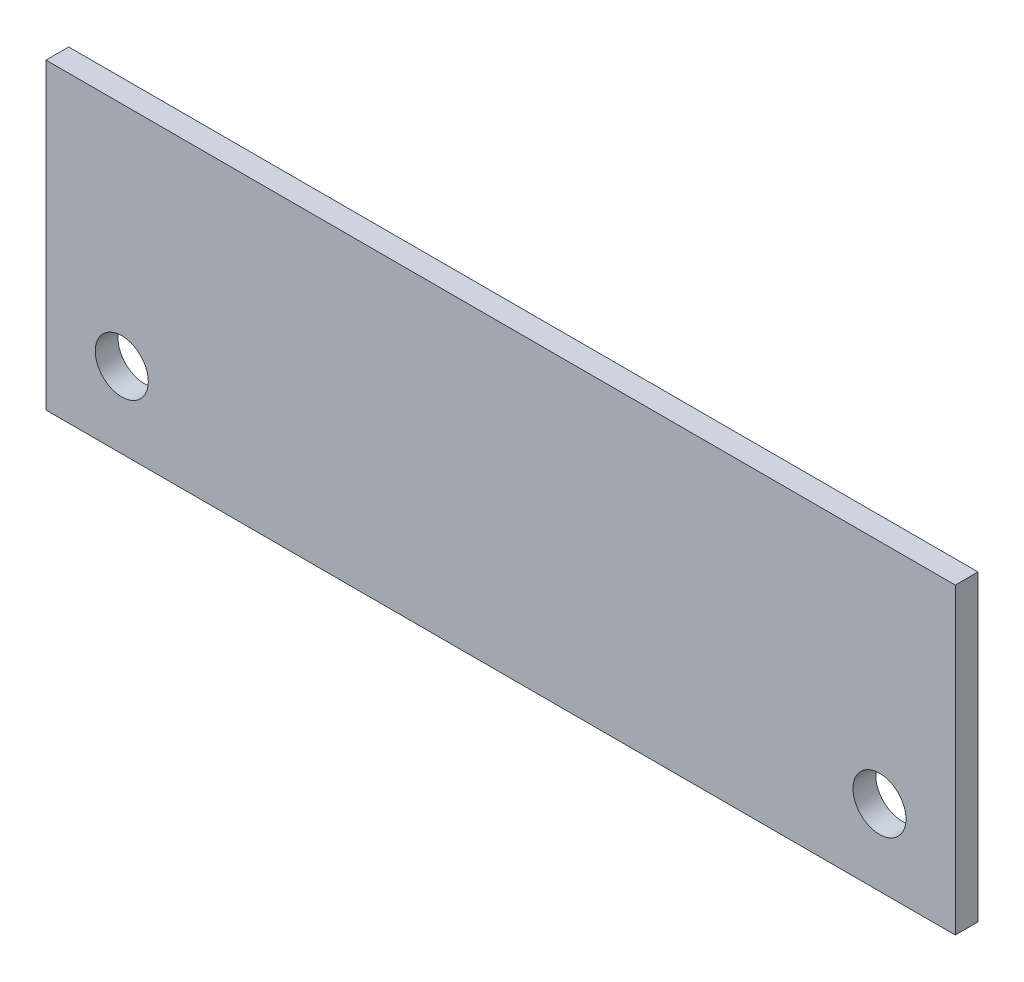
SolidWorks part; units mm, degrees
material "ASTM A36 Steel"
ref_plane "Front Plane" through (0, 0, 0) normal (0, 0, 1) x (1, 0, 0)
ref_plane "Top Plane" through (0, 0, 0) normal (0, 1, 0) x (1, 0, 0)
ref_plane "Right Plane" through (0, 0, 0) normal (1, 0, 0) x (0, 0, -1)
sketch "Sketch1" plane through (0, 0, 0) normal (0, 0, 1) x (1, 0, 0)
  line L1 (-120, -40) -> (120, -40)
  line L2 (-120, -40) -> (-120, 40)
  line L3 (-120, 40) -> (120, 40)
  line L4 (120, -40) -> (120, 40)
  line L5 (-120, -40) -> (120, 40) construction
  line L6 (-120, 40) -> (120, -40) construction
  circle A0 centre (-100, -20) radius 7
  circle A1 centre (100, -20) radius 7
  point P0 (0, 0)
  dimension "D3" = 14
  dimension "D4" = 14
  dimension "D5" = 20
  dimension "D6" = 20
  dimension "D7" = 20
  dimension "D8" = 20
  dimension "D1" = 240
  dimension "D2" = 80
extrude "Boss-Extrude1" add sketch "Sketch1" along normal blind 6
